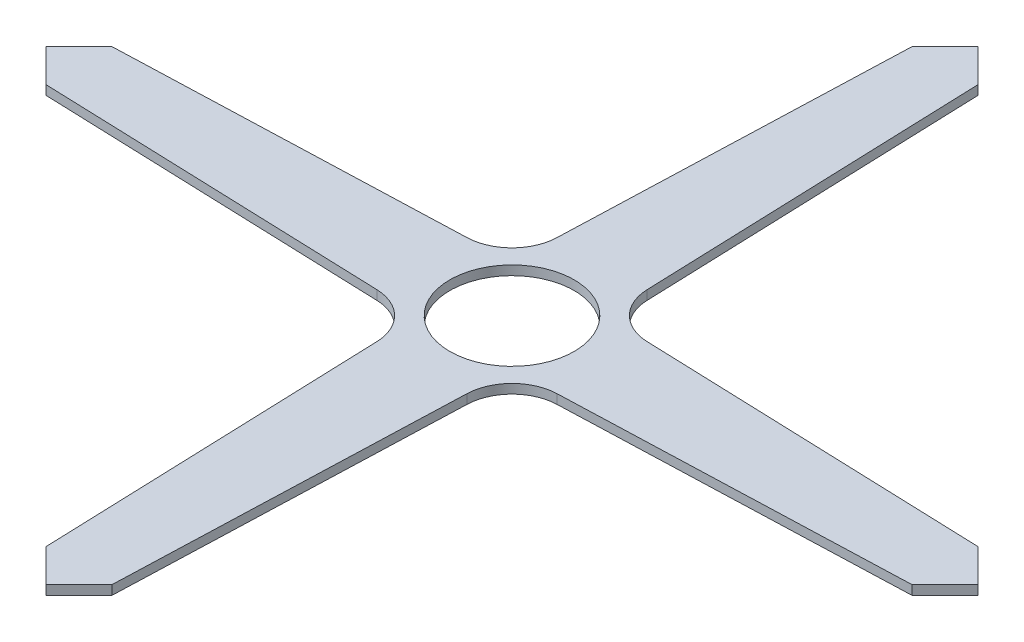
SolidWorks part; units mm, degrees
ref_plane "Front Plane" through (0, 0, 0) normal (0, 0, 1) x (1, 0, 0)
ref_plane "Top Plane" through (0, 0, 0) normal (0, 1, 0) x (1, 0, 0)
ref_plane "Right Plane" through (0, 0, 0) normal (1, 0, 0) x (0, 0, -1)
sketch "Sketch1" plane through (0, 0, 0) normal (0, 1, 0) x (1, 0, 0)
  line L0 (-286.26, 15) -> (-410.6534, 10.6066)
  line L1 (-410.6534, -10.6066) -> (-421.26, 0)
  line L2 (-410.6534, -10.6066) -> (-286.26, -15)
  line L3 (-256.26, 15) -> (-260.6534, 139.3934)
  line L4 (-281.8666, 139.3934) -> (-271.26, 150)
  line L5 (-281.8666, 139.3934) -> (-286.26, 15)
  line L6 (-271.26, 150) -> (-260.6534, 139.3934)
  line L7 (-256.26, -15) -> (-131.8666, -10.6066)
  line L8 (-131.8666, 10.6066) -> (-121.26, 0)
  line L9 (-131.8666, 10.6066) -> (-256.26, 15)
  line L10 (-121.26, 0) -> (-131.8666, -10.6066)
  line L11 (-286.26, -15) -> (-281.8666, -139.3934)
  line L12 (-260.6534, -139.3934) -> (-271.26, -150)
  line L13 (-260.6534, -139.3934) -> (-256.26, -15)
  line L14 (-271.26, -150) -> (-281.8666, -139.3934)
  line L15 (-421.26, 0) -> (-410.6534, 10.6066)
  line L16 (-121.26, 0) -> (-421.26, 0) construction
  line L17 (-271.26, -150) -> (-271.26, 150) construction
  circle A0 centre (-271.26, 0) radius 20
  point P24 (-271.26, 0)
  dimension "D9" = 15
  dimension "D2" = 40
  dimension "D3" = 90
  dimension "D4" = 15
  dimension "D5" = 15
  dimension "D10" = 15
  dimension "D11" = 150
  dimension "D8" = 4
extrude "Boss-Extrude1" add sketch "Sketch1" along normal blind 3
fillet "Fillet1" radius 15 4 edges at (-286.26, 1.5, -15) (-256.26, 1.5, -15) (-286.26, 1.5, 15) (-256.26, 1.5, 15)
